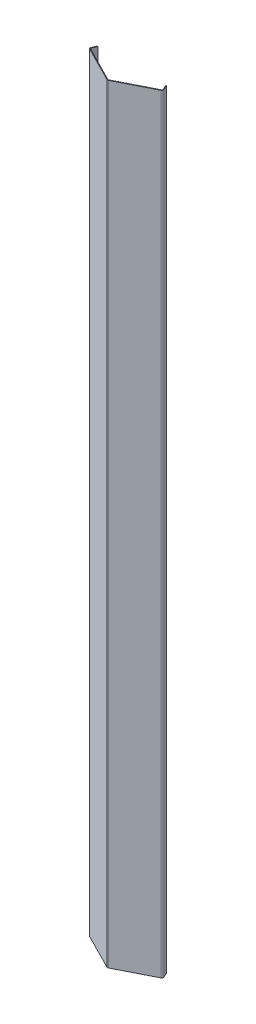
SolidWorks part; units mm, degrees
material "ASTM A36 Steel"
ref_plane "Front Plane" through (0, 0, 0) normal (0, 0, 1) x (1, 0, 0)
ref_plane "Top Plane" through (0, 0, 0) normal (0, 1, 0) x (1, 0, 0)
ref_plane "Right Plane" through (0, 0, 0) normal (1, 0, 0) x (0, 0, -1)
sketch "Sketch1" plane through (0, 0, 0) normal (0, 1, 0) x (1, 0, 0)
  line L3 (319.2222, 134.9653) -> (331.4949, 107.6505)
  line L5 (112.7099, -13.8833) -> (326.8928, 94.6317)
  line L15 (-99.1928, 133.3259) -> (-111.4654, 106.0111)
  line L16 (105.4787, -10.3152) -> (-108.7041, 98.1998)
  line L17 (110.9021, -10.3152) -> (325.085, 98.1998)
  line L18 (315.5736, 133.3259) -> (327.8462, 106.0111)
  line L20 (103.6709, -13.8833) -> (-110.5119, 94.6317)
  line L21 (-102.8414, 134.9653) -> (-115.114, 107.6505)
  line L22 (-102.8414, 134.9653) -> (-99.1928, 133.3259)
  line L23 (319.2222, 134.9653) -> (315.5736, 133.3259)
  arc A0 (331.4949, 107.6505) -> (326.8928, 94.6317) centre (322.3733, 103.5521) cw
  arc A2 (103.6709, -13.8833) -> (112.7099, -13.8833) centre (108.1904, -4.9629) ccw
  arc A6 (-111.4654, 106.0111) -> (-108.7041, 98.1998) centre (-105.9924, 103.5521) ccw
  arc A7 (105.4787, -10.3152) -> (110.9021, -10.3152) centre (108.1904, -4.9629) ccw
  arc A8 (327.8462, 106.0111) -> (325.085, 98.1998) centre (322.3733, 103.5521) cw
  arc A11 (-115.114, 107.6505) -> (-110.5119, 94.6317) centre (-105.9924, 103.5521) ccw
  point P7 (335.4063, 98.945)
  point P31 (-119.0254, 98.945)
  dimension "D2" = 10
  dimension "D1" = 4
extrude "Boss-Extrude2" add sketch "Sketch1" along normal blind 4710
